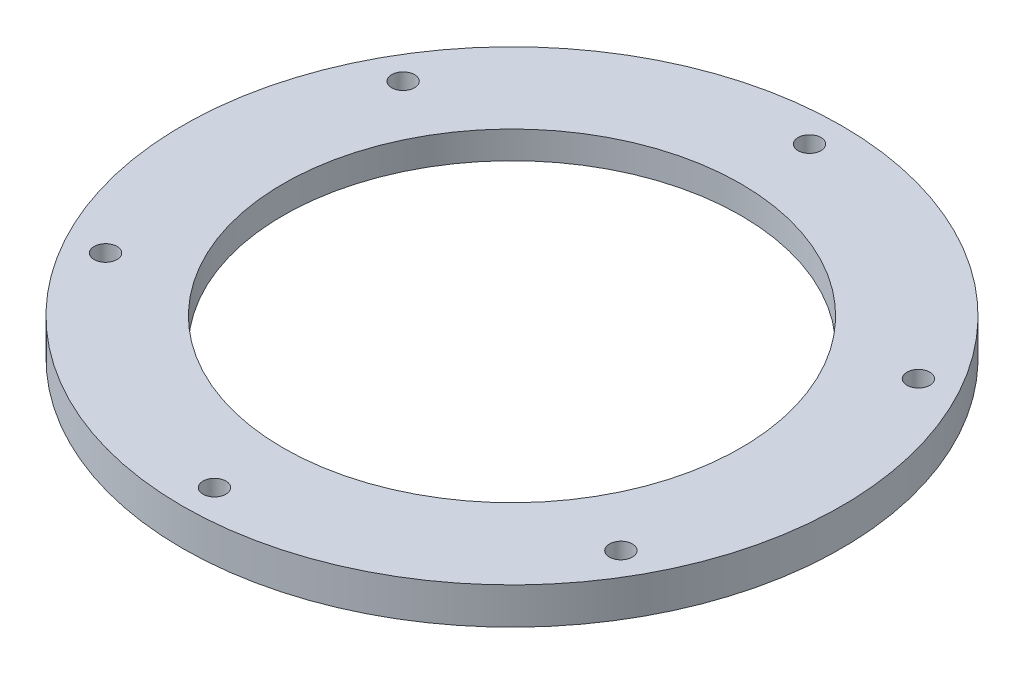
SolidWorks part; units mm, degrees
ref_plane "前视基准面" through (0, 0, 0) normal (0, 0, 1) x (1, 0, 0)
ref_plane "上视基准面" through (0, 0, 0) normal (0, 1, 0) x (1, 0, 0)
ref_plane "右视基准面" through (0, 0, 0) normal (1, 0, 0) x (0, 0, -1)
sketch "草图1" plane through (0, 0, 0) normal (0, 1, 0) x (1, 0, 0)
  circle A0 centre (0, 0) radius 25
  circle A1 centre (0, 0) radius 36
  point P19 (0, 0)
  point P23 (0, 0)
  dimension "D1" = 50
  dimension "D2" = 72
extrude "凸台-拉伸1" add sketch "草图1" along normal blind 3
sketch "草图3" plane through (0, 0, 0) normal (0, -1, 0) x (1, 0, 0)
  circle A0 centre (0, 0) radius 36
  circle A1 centre (0, 0) radius 35
  dimension "D1" = 70
extrude "凸台-拉伸2" add sketch "草图3" along normal blind 1
sketch "草图4" plane through (0, 0, 0) normal (0, -1, 0) x (1, 0, 0)
  circle A0 centre (0, 0) radius 32.5
  circle A1 centre (0, 32.5) radius 1.25
  circle A2 centre (0, 0) radius 32.5
  circle A3 centre (0, 0) radius 32.5
  circle A4 centre (0, 0) radius 32.5
  circle A5 centre (0, 0) radius 32.5
  circle A6 centre (0, 0) radius 32.5
  circle A7 centre (28.1458, 16.25) radius 1.25
  circle A8 centre (28.1458, -16.25) radius 1.25
  circle A9 centre (0, -32.5) radius 1.25
  circle A10 centre (-28.1458, -16.25) radius 1.25
  circle A11 centre (-28.1458, 16.25) radius 1.25
  point P20 (0, 0)
  point P30 (0, 0)
  dimension "D1" = 65
  dimension "D2" = 2.5
  dimension "D3" = 6
  dimension "D4" = 6
hole_wizard "M2.5 螺纹孔1" positions "3D草图2" profile "草图6" tap size "M2.5" standard "ISO" end condition through all
sketch3d "3D草图2"
  point P0 (0, 0, 32.5)
  point P3 (28.1458, 0, 16.25)
  point P6 (28.1458, 0, -16.25)
  point P9 (-28.1458, 0, 16.25)
  point P12 (-28.1458, 0, -16.25)
  point P15 (0, 0, -32.5)
sketch "草图6" plane through (0, 0, 32.5) normal (1, 0, 0) x (0, 0, -1)
  line L0 (0, 0) -> (0, 3)
  line L1 (0, 3) -> (1.25, 3)
  line L2 (1.25, 3) -> (1.25, 0)
  line L5 (1.25, 0) -> (0, 0)
  line L11 (0, -6.35) -> (0, 107.95) construction
  dimension "通孔螺纹孔钻头直径" = 2.5
  dimension "通孔螺纹孔钻头深度" = 3
cosmetic thread "孔螺蚊线1" parameters "D2"=2.5
cosmetic thread "孔螺蚊线2" parameters "D2"=2.5
cosmetic thread "孔螺蚊线3" parameters "D2"=2.5
cosmetic thread "孔螺蚊线4" parameters "D2"=2.5
cosmetic thread "孔螺蚊线5" parameters "D2"=2.5
cosmetic thread "孔螺蚊线6" parameters "D2"=2.5
